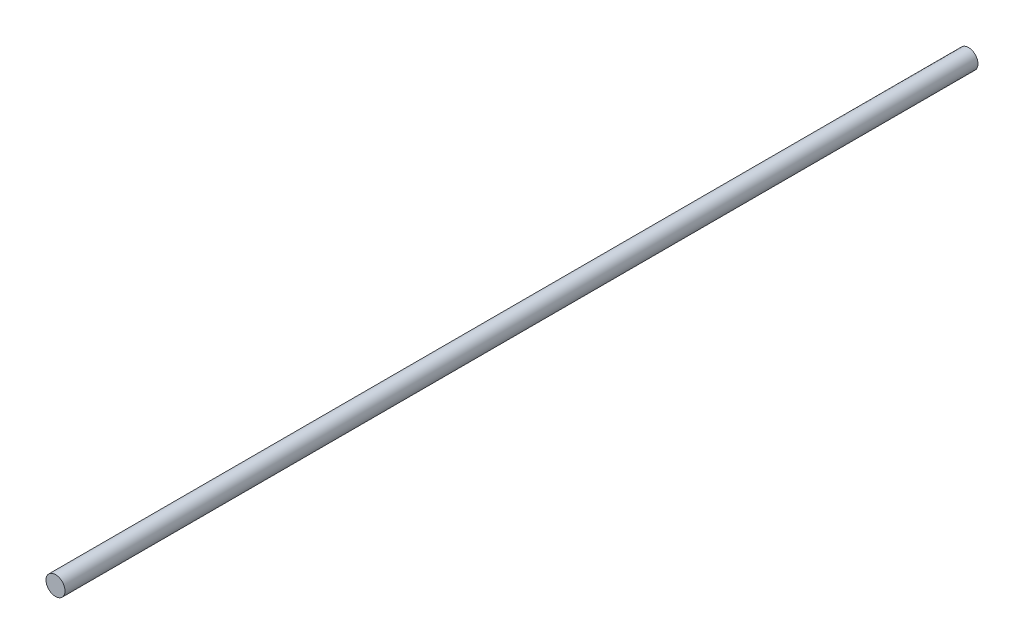
SolidWorks part; units mm, degrees
ref_plane "Front Plane" through (0, 0, 0) normal (0, 0, 1) x (1, 0, 0)
ref_plane "Top Plane" through (0, 0, 0) normal (0, 1, 0) x (1, 0, 0)
ref_plane "Right Plane" through (0, 0, 0) normal (1, 0, 0) x (0, 0, -1)
sketch "Sketch1" plane through (0, 0, 0) normal (0, 0, 1) x (1, 0, 0)
  circle A0 centre (0, 0) radius 2
  dimension "D1" = 4
extrude "Boss-Extrude1" add sketch "Sketch1" along normal blind 192
